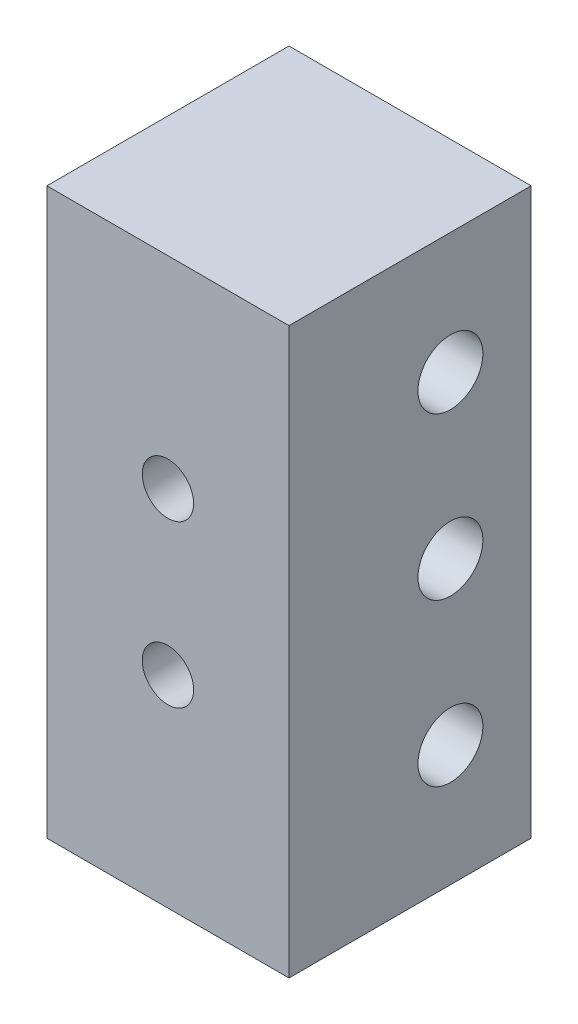
SolidWorks part; units mm, degrees
material "6061-T6 (SS)"
ref_plane "Front Plane" through (0, 0, 0) normal (0, 0, 1) x (1, 0, 0)
ref_plane "Top Plane" through (0, 0, 0) normal (0, 1, 0) x (1, 0, 0)
ref_plane "Right Plane" through (0, 0, 0) normal (1, 0, 0) x (0, 0, -1)
sketch "Sketch1" plane through (0, 0, 0) normal (0, 1, 0) x (1, 0, 0)
  line L1 (0, 0) -> (19.05, 0)
  line L2 (0, 0) -> (0, 19.05)
  line L3 (0, 19.05) -> (19.05, 19.05)
  line L4 (19.05, 0) -> (19.05, 19.05)
  dimension "D1" = 19.05
  dimension "D2" = 19.05
extrude "Boss-Extrude1" add sketch "Sketch1" along normal mid plane 44.45
sketch "Sketch2" plane through (0, 0, 0) normal (-1, 0, 0) x (0, 0, 1)
  line L0 (-12.7, -22.225) -> (-12.7, 22.225) construction
  line L1 (-19.05, -22.225) -> (0, -22.225) construction
  line L2 (-19.05, 22.225) -> (0, 22.225) construction
  line L3 (0, 22.225) -> (0, -22.225) construction
  circle A0 centre (-12.7, 12.7) radius 2.5527
  circle A1 centre (-12.7, -12.7) radius 2.5527
  circle A2 centre (-12.7, 0) radius 2.5527
  dimension "D2" = 5.1054
  dimension "D1" = 12.7
  dimension "D3" = 9.525
  dimension "D4" = 12.7
  dimension "D5" = 12.7
extrude "Cut-Extrude1" cut sketch "Sketch2" against normal through all
hole_wizard "#10-32 Tapped Hole1" positions "3DSketch1" profile "Sketch3" tap size "#10-32" standard "ANSI Inch" end condition through all
sketch3d "3DSketch1"
  line L0 (9.525, 22.225, -19.05) -> (9.525, -22.225, -19.05) construction
  line L1 (19.05, 22.225, -19.05) -> (0, 22.225, -19.05) construction
  line L2 (19.05, -22.225, -19.05) -> (0, -22.225, -19.05) construction
  point P0 (9.525, -6.35, -19.05)
  point P2 (9.525, 6.35, -19.05)
  dimension "D1" = 15.875
  dimension "D2" = 12.7
sketch "Sketch3" plane through (9.525, -6.35, -19.05) normal (1, 0, 0) x (0, 1, 0)
  line L0 (0, 0) -> (0, 19.05)
  line L1 (0, 19.05) -> (2.0193, 19.05)
  line L2 (2.0193, 19.05) -> (2.0193, 0)
  line L5 (2.0193, 0) -> (0, 0)
  line L11 (0, -6.35) -> (0, 107.95) construction
  dimension "Thru Tap Drill Dia." = 4.0386
  dimension "Thru Tap Drill Depth" = 19.05
cosmetic thread "Hole Thread1" parameters "D2"=4.826
cosmetic thread "Hole Thread2" parameters "D2"=4.826
